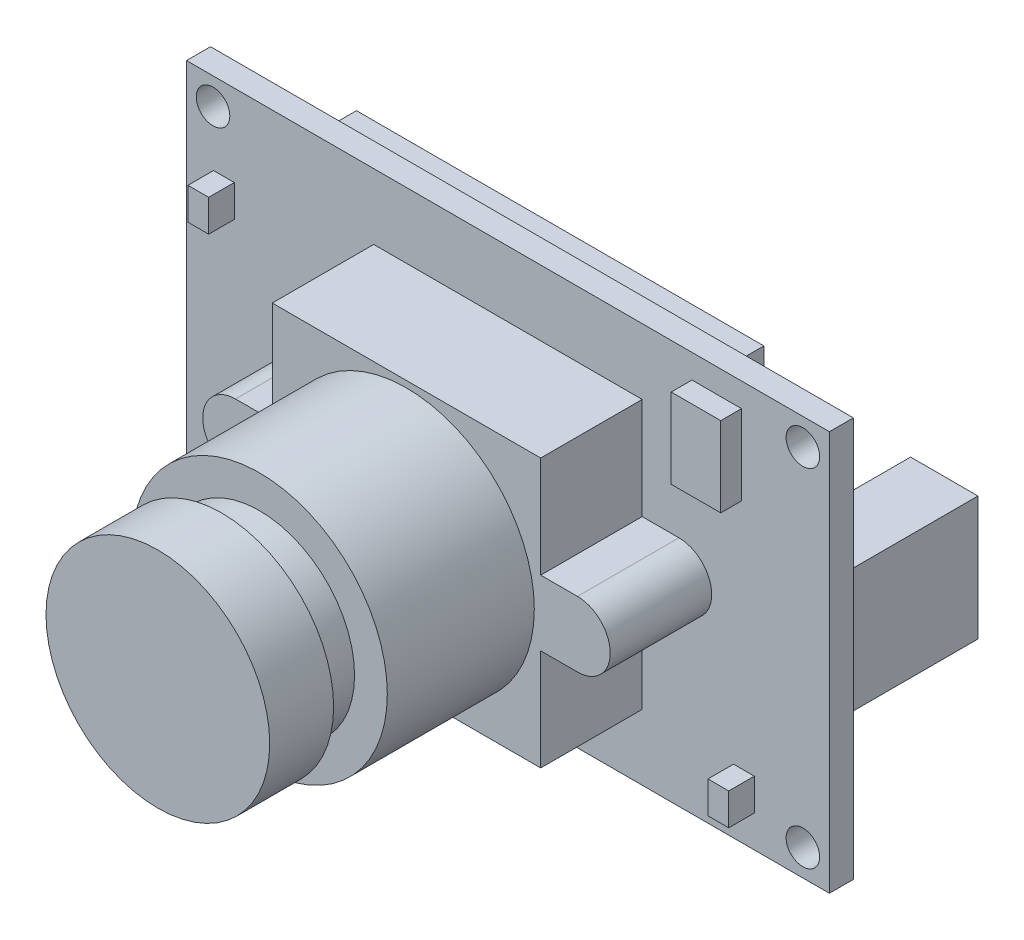
SolidWorks part; units mm, degrees
ref_plane "Front Plane" through (0, 0, 0) normal (0, 0, 1) x (1, 0, 0)
ref_plane "Top Plane" through (0, 0, 0) normal (0, 1, 0) x (1, 0, 0)
ref_plane "Right Plane" through (0, 0, 0) normal (1, 0, 0) x (0, 0, -1)
sketch "Sketch2" plane through (0, 0, 0) normal (0, 0, 1) x (1, 0, 0)
  line L0 (0, 0) -> (0, 6.003) construction
  line L1 (20.1168, 12.5095) -> (-20.1168, 12.5095)
  line L2 (20.1168, 12.5095) -> (20.1168, -12.5095)
  line L3 (20.1168, -12.5095) -> (-20.1168, -12.5095)
  line L4 (-20.1168, 12.5095) -> (-20.1168, -12.5095)
  line L5 (20.1168, 12.5095) -> (-20.1168, -12.5095) construction
  line L6 (20.1168, -12.5095) -> (-20.1168, 12.5095) construction
  line L7 (-1000, 0) -> (49000, 0) construction
  circle A0 centre (-18.4568, 10.8495) radius 1.05
  circle A1 centre (-18.4568, -10.8495) radius 1.05
  circle A2 centre (18.4568, -10.8495) radius 1.05
  circle A3 centre (18.4568, 10.8495) radius 1.05
  point P0 (0, 0)
  dimension "D5" = 2.1
  dimension "D1" = 40.2336
  dimension "D2" = 25.019
  dimension "D3" = 1.66
  dimension "D4" = 1.66
extrude "Boss-Extrude1" add sketch "Sketch2" along normal blind 1.5
sketch "Sketch3" plane through (0, 0, 1.5) normal (0, 0, 1) x (1, 0, 0)
  line L0 (-8.4, -2.05) -> (-8.4, -8.4)
  line L1 (8.4, 8.4) -> (-8.4, 8.4)
  line L2 (8.4, 8.4) -> (8.4, 2.05)
  line L3 (8.4, -8.4) -> (-8.4, -8.4)
  line L4 (-8.4, 8.4) -> (-8.4, 2.05)
  line L5 (8.4, 8.4) -> (-8.4, -8.4) construction
  line L6 (8.4, -8.4) -> (-8.4, 8.4) construction
  line L7 (-10.7, 2.05) -> (-8.4, 2.05)
  line L8 (0, -1000) -> (0, 49000) construction
  line L9 (-10.7, -2.05) -> (-8.4, -2.05)
  line L10 (10.7, 2.05) -> (8.4, 2.05)
  line L11 (10.7, -2.05) -> (8.4, -2.05)
  line L12 (8.4, -2.05) -> (8.4, -8.4)
  line L13 (-1000, 0) -> (49000, 0) construction
  arc A0 (-10.7, 2.05) -> (-10.7, -2.05) centre (-10.7, 0) ccw
  arc A1 (10.7, 2.05) -> (10.7, -2.05) centre (10.7, 0) cw
  point P0 (0, 0)
  dimension "D1" = 16.8
  dimension "D2" = 16.8
  dimension "D3" = 4.1
  dimension "D4" = 2.3
extrude "Boss-Extrude2" add sketch "Sketch3" along normal blind 6.35
sketch "Sketch4" plane through (0, 0, 7.85) normal (0, 0, 1) x (1, 0, 0)
  circle A0 centre (0, 0) radius 8
  dimension "D1" = 16
extrude "Boss-Extrude3" add sketch "Sketch4" along normal blind 9.2
sketch "Sketch5" plane through (0, 0, 17.05) normal (0, 0, 1) x (1, 0, 0)
  circle A0 centre (0, 0) radius 5.95
  dimension "D1" = 11.9
extrude "Boss-Extrude4" add sketch "Sketch5" along normal blind 2.36
sketch "Sketch6" plane through (0, 0, 19.41) normal (0, 0, 1) x (1, 0, 0)
  circle A0 centre (0, 0) radius 7
extrude "Boss-Extrude5" add sketch "Sketch6" along normal blind 4
sketch "Sketch7" plane through (0, 0, 0) normal (0, 0, -1) x (-1, 0, 0)
  line L0 (0, 0) -> (-20.1168, 0) construction
  line L1 (-15.3968, -3.875) -> (-19.6168, -3.875)
  line L2 (-15.3968, -3.875) -> (-15.3968, 3.875)
  line L3 (-15.3968, 3.875) -> (-19.6168, 3.875)
  line L4 (-19.6168, -3.875) -> (-19.6168, 3.875)
  line L5 (-20.1168, -12.5095) -> (-20.1168, 12.5095) construction
  point P9 (-19.6168, 0)
  dimension "D1" = 7.75
  dimension "D2" = 4.22
  dimension "D3" = 0.5
extrude "Boss-Extrude6" add sketch "Sketch7" along normal blind 8.3
sketch "Sketch8" plane through (0, 0, 0) normal (0, 0, -1) x (-1, 0, 0)
  line L0 (20.1168, 12.5095) -> (20.1168, -12.5095) construction
  line L1 (15.6768, -10.8695) -> (6.6768, -10.8695)
  line L2 (15.6768, -10.8695) -> (15.6768, -7.9395)
  line L3 (15.6768, -7.9395) -> (6.6768, -7.9395)
  line L4 (6.6768, -10.8695) -> (6.6768, -7.9395)
  line L5 (20.1168, -12.5095) -> (-20.1168, -12.5095) construction
  dimension "D1" = 4.44
  dimension "D2" = 1.64
  dimension "D3" = 9
  dimension "D4" = 2.93
extrude "Boss-Extrude7" add sketch "Sketch8" along normal blind 4.35
sketch "Sketch9" plane through (0, 0, 1.5) normal (0, 0, 1) x (1, 0, 0)
  line L0 (20.1168, -12.5095) -> (20.1168, 12.5095) construction
  line L1 (11.5168, 11.0095) -> (14.6168, 11.0095)
  line L2 (11.5168, 11.0095) -> (11.5168, 6.0095)
  line L3 (11.5168, 6.0095) -> (14.6168, 6.0095)
  line L4 (14.6168, 11.0095) -> (14.6168, 6.0095)
  line L5 (20.1168, 12.5095) -> (-20.1168, 12.5095) construction
  dimension "D1" = 3.1
  dimension "D2" = 5
  dimension "D3" = 5.5
  dimension "D4" = 1.5
extrude "Boss-Extrude8" add sketch "Sketch9" along normal blind 1.3
sketch "Sketch10" plane through (0, 0, 0) normal (0, 0, -1) x (-1, 0, 0)
  line L0 (-20.1168, -12.5095) -> (-20.1168, 12.5095) construction
  line L1 (-13.1168, 12.2095) -> (12.3832, 12.2095)
  line L2 (-13.1168, 12.2095) -> (-13.1168, 4.2095)
  line L3 (-13.1168, 4.2095) -> (12.3832, 4.2095)
  line L4 (12.3832, 12.2095) -> (12.3832, 4.2095)
  line L5 (-13.1168, 12.2095) -> (12.3832, 4.2095) construction
  line L6 (-13.1168, 4.2095) -> (12.3832, 12.2095) construction
  line L7 (-20.1168, 12.5095) -> (20.1168, 12.5095) construction
  point P0 (-0.3668, 8.2095)
  dimension "D1" = 25.5
  dimension "D2" = 8
  dimension "D3" = 7
  dimension "D4" = 0.3
extrude "Boss-Extrude9" add sketch "Sketch10" along normal blind 1.4
sketch "Sketch11" plane through (0, 0, 1.5) normal (0, 0, 1) x (1, 0, 0)
  line L0 (20.1168, -12.5095) -> (20.1168, 12.5095) construction
  line L1 (15.4168, -10.5095) -> (14.1168, -10.5095)
  line L2 (15.4168, -10.5095) -> (15.4168, -8.5095)
  line L3 (15.4168, -8.5095) -> (14.1168, -8.5095)
  line L4 (14.1168, -10.5095) -> (14.1168, -8.5095)
  line L5 (-20.1168, -12.5095) -> (20.1168, -12.5095) construction
  line L6 (-17.1271, 5.3916) -> (-18.4271, 5.3916)
  line L7 (-17.1271, 5.3916) -> (-17.1271, 7.3916)
  line L8 (-17.1271, 7.3916) -> (-18.4271, 7.3916)
  line L9 (-18.4271, 5.3916) -> (-18.4271, 7.3916)
  dimension "D1" = 1.3
  dimension "D2" = 2
  dimension "D3" = 6
  dimension "D4" = 2
extrude "Boss-Extrude10" add sketch "Sketch11" along normal blind 1.6
sketch "Sketch12" plane through (0, 0, 0) normal (0, 0, -1) x (-1, 0, 0)
  line L0 (-20.1168, 12.5095) -> (20.1168, 12.5095) construction
  line L1 (19.1168, 5.1095) -> (16.1168, 5.1095)
  line L2 (19.1168, 5.1095) -> (19.1168, 8.1095)
  line L3 (19.1168, 8.1095) -> (16.1168, 8.1095)
  line L4 (16.1168, 5.1095) -> (16.1168, 8.1095)
  line L5 (20.1168, 12.5095) -> (20.1168, -12.5095) construction
  dimension "D1" = 3
  dimension "D2" = 3
  dimension "D3" = 7.4
  dimension "D4" = 1
extrude "Boss-Extrude11" add sketch "Sketch12" along normal blind 1.4
